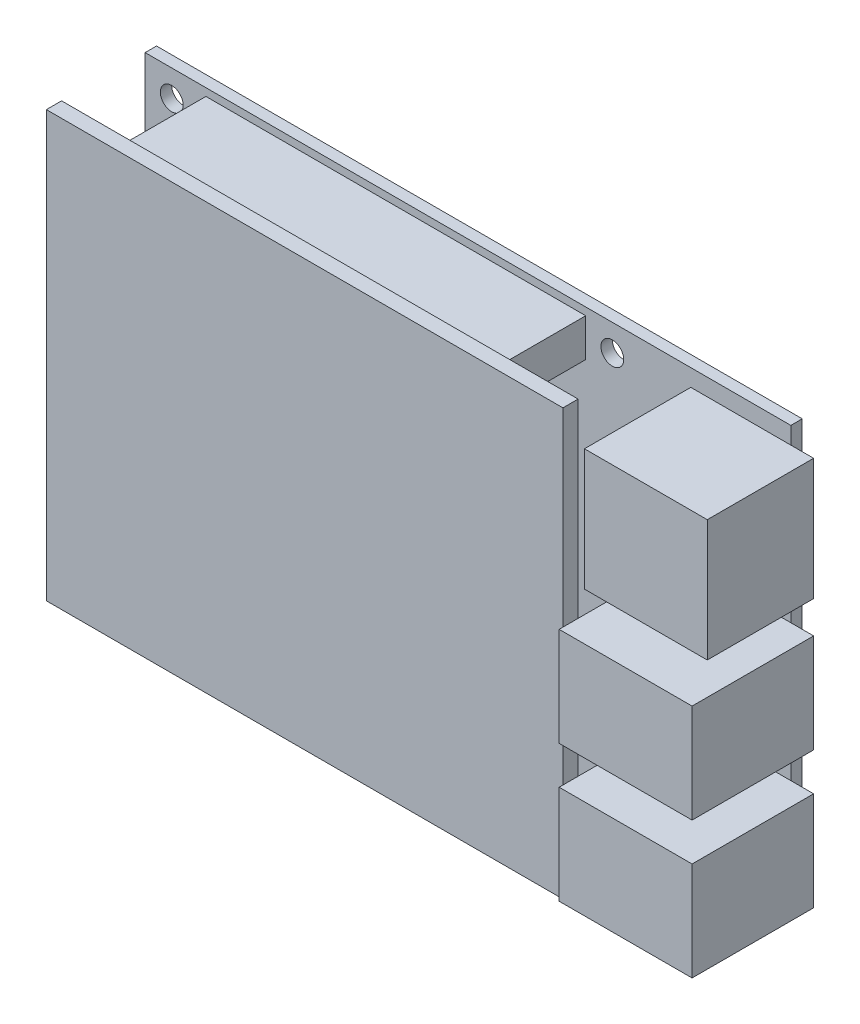
SolidWorks part; units mm, degrees
ref_plane "Front Plane" through (0, 0, 0) normal (0, 0, 1) x (1, 0, 0)
ref_plane "Top Plane" through (0, 0, 0) normal (0, 1, 0) x (1, 0, 0)
ref_plane "Right Plane" through (0, 0, 0) normal (1, 0, 0) x (0, 0, -1)
sketch "Sketch1" plane through (0, 0, 0) normal (0, 0, 1) x (1, 0, 0)
  line L1 (0, 0) -> (85, 0)
  line L2 (0, 0) -> (0, 56)
  line L3 (0, 56) -> (85, 56)
  line L4 (85, 0) -> (85, 56)
  dimension "D1" = 85
  dimension "D2" = 56
extrude "Boss-Extrude1" add sketch "Sketch1" along normal blind 1.5
sketch "Sketch2" plane through (0, 0, 1.5) normal (0, 0, 1) x (1, 0, 0)
  line L0 (0, 56) -> (0, 0) construction
  line L1 (85, 56) -> (0, 56) construction
  line L2 (0, 0) -> (85, 0) construction
  circle A0 centre (3.5, 52.5) radius 1.5
  circle A1 centre (3.5, 3.5) radius 1.5
  circle A2 centre (61.5, 52.5) radius 1.5
  circle A3 centre (61.5, 3.5) radius 1.5
  dimension "D6" = 3
  dimension "D7" = 3
  dimension "D8" = 3
  dimension "D9" = 3
  dimension "D1" = 58
  dimension "D2" = 3.5
  dimension "D3" = 3.5
  dimension "D4" = 3.5
  dimension "D5" = 3.5
  dimension "D10" = 3.5
  dimension "D11" = 3.5
  dimension "D12" = 58
extrude "Cut-Extrude1" cut sketch "Sketch2" against normal through all
sketch "Sketch3" plane through (0, 0, 1.5) normal (0, 0, 1) x (1, 0, 0)
  line L1 (73.0254, 27) -> (103.6599, 27) construction
  line L2 (73.0254, 9) -> (103.6599, 9) construction
  line L3 (0, 0) -> (85, 0) construction
  line L4 (88, 15.5) -> (70.5, 15.5)
  line L5 (88, 15.5) -> (88, 2.5)
  line L6 (88, 2.5) -> (70.5, 2.5)
  line L7 (70.5, 15.5) -> (70.5, 2.5)
  line L8 (88, 33.5) -> (70.5, 33.5)
  line L9 (88, 33.5) -> (88, 20.5)
  line L10 (88, 20.5) -> (70.5, 20.5)
  line L11 (70.5, 33.5) -> (70.5, 20.5)
  line L16 (85, 0) -> (85, 56) construction
  dimension "D1" = 9
  dimension "D2" = 27
  dimension "D3" = 6.5
  dimension "D4" = 13
  dimension "D5" = 13
  dimension "D6" = 6.5
  dimension "D7" = 17.5
  dimension "D8" = 17.5
  dimension "D9" = 3
  dimension "D10" = 3
extrude "Boss-Extrude3" add sketch "Sketch3" along normal blind 16
sketch "Sketch4" plane through (0, 0, 1.5) normal (0, 0, 1) x (1, 0, 0)
  line L0 (71.0274, 45.75) -> (102.9866, 45.75) construction
  line L1 (0, 0) -> (85, 0) construction
  line L2 (71.8314, 53.75) -> (88, 53.75)
  line L3 (71.8314, 53.75) -> (71.8314, 37.75)
  line L4 (71.8314, 37.75) -> (88, 37.75)
  line L5 (88, 53.75) -> (88, 37.75)
  line L6 (85, 33.5) -> (85, 56) construction
  dimension "D1" = 45.75
  dimension "D2" = 8
  dimension "D3" = 16
  dimension "D4" = 3
extrude "Boss-Extrude4" add sketch "Sketch4" along normal blind 14
sketch "Sketch5" plane through (0, 0, 1.5) normal (0, 0, 1) x (1, 0, 0)
  line L0 (0, 56) -> (0, 0) construction
  line L1 (8, 55) -> (58, 55)
  line L2 (8, 55) -> (8, 50)
  line L3 (8, 50) -> (58, 50)
  line L4 (58, 55) -> (58, 50)
  line L5 (85, 56) -> (0, 56) construction
  dimension "D1" = 5
  dimension "D2" = 50
  dimension "D3" = 8
  dimension "D4" = 1
extrude "Boss-Extrude5" add sketch "Sketch5" along normal blind 11
sketch "Sketch6" plane through (0, 0, 12.5) normal (0, 0, 1) x (1, 0, 0)
  line L0 (58, 55) -> (8, 55) construction
  line L1 (68, 56) -> (0, 56)
  line L2 (68, 56) -> (68, 0)
  line L3 (68, 0) -> (0, 0)
  line L4 (0, 56) -> (0, 0)
  line L5 (58, 50) -> (58, 55) construction
  line L6 (0, 56) -> (0, 0) construction
  dimension "D1" = 56
  dimension "D2" = 1
  dimension "D3" = 10
  dimension "D4" = 0
extrude "Boss-Extrude6" add sketch "Sketch6" along normal blind 2
